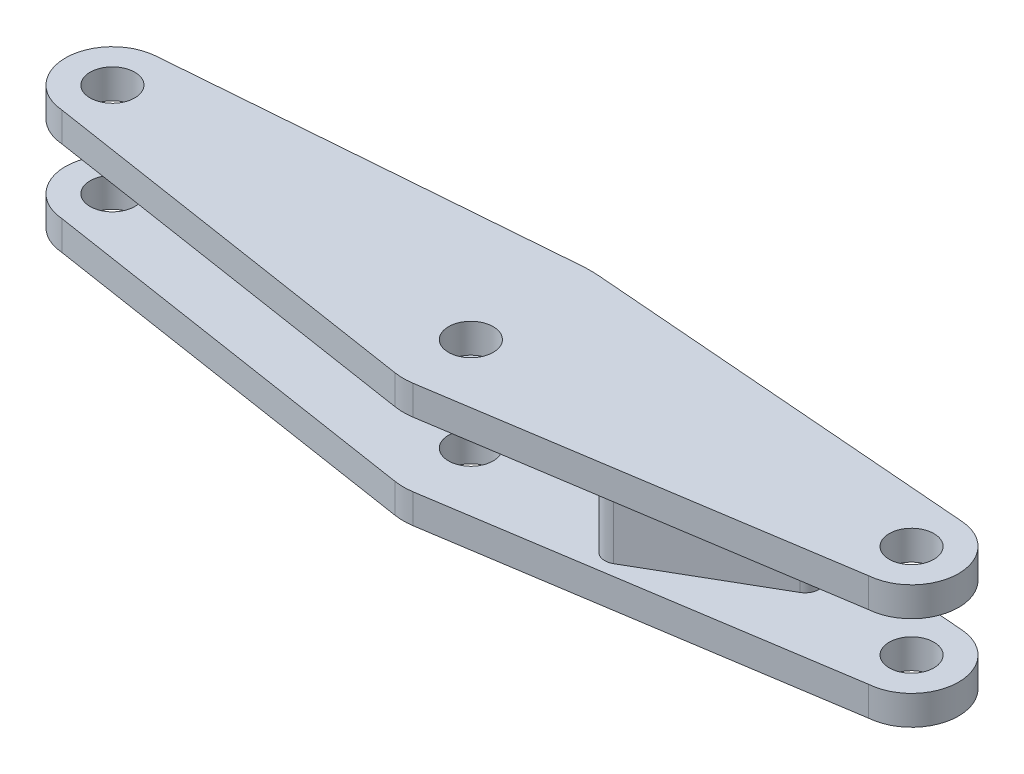
SolidWorks part; units mm, degrees
ref_plane "Front Plane" through (0, 0, 0) normal (0, 0, 1) x (1, 0, 0)
ref_plane "Top Plane" through (0, 0, 0) normal (0, 1, 0) x (1, 0, 0)
ref_plane "Right Plane" through (0, 0, 0) normal (1, 0, 0) x (0, 0, -1)
sketch "Sketch1" plane through (0, 0, 0) normal (0, 1, 0) x (1, 0, 0)
  line L0 (17, 0) -> (-15, 0) construction
  line L1 (0, 0) -> (0, 3.35) construction
  line L2 (0, 0) -> (0, -4.65) construction
  line L3 (-0.394, 3.3189) -> (-17.1576, 1.9938)
  line L4 (0.394, 3.3189) -> (17.1576, 1.9938)
  line L7 (-16.05, 0) -> (-17, 0) construction
  line L10 (-0.3825, -4.5908) -> (-17.1576, -1.9938)
  line L11 (0.3825, -4.5908) -> (17.1576, -1.9938)
  arc A0 (-17.1576, 1.9938) -> (-17.1576, -1.9938) centre (-17, 0) ccw
  circle A1 centre (-17, 0) radius 0.95
  circle A2 centre (17, 0) radius 0.95
  arc A3 (17.1576, -1.9938) -> (17.1576, 1.9938) centre (17, 0) ccw
  arc A4 (0.394, 3.3189) -> (-0.394, 3.3189) centre (0, -1.6656) ccw
  circle A6 centre (0, -1.75) radius 0.95
  arc A7 (0.3825, -4.5908) -> (-0.3825, -4.5908) centre (0, -2.1202) cw
  point P20 (0, 3.3344)
  point P21 (0, 3.3344)
  point P25 (0, 3.35)
  point P26 (0, 3.3344)
  dimension "D1" = 34
  dimension "D4" = 4
  dimension "D5" = 1.9
  dimension "D6" = 4
  dimension "D7" = 1.9
  dimension "D8" = 5
  dimension "D9" = 2.5
  dimension "D10" = 1.75
  dimension "D11" = 1.9
  dimension "D12" = 1.9944
  dimension "D2" = 8
  dimension "D3" = 3.35
extrude "Boss-Extrude1" add sketch "Sketch1" along normal mid plane 5.25
sketch "Sketch3" plane through (0, 0, 0) normal (0, 0, 1) x (1, 0, 0)
  line L0 (-19, 2.625) -> (-19, -2.625) construction
  line L1 (19, 1.375) -> (-19, 1.375)
  line L2 (19, 1.375) -> (19, -1.375)
  line L3 (19, -1.375) -> (-19, -1.375)
  line L4 (-19, 1.375) -> (-19, -1.375)
  line L5 (19, 1.375) -> (-19, -1.375) construction
  line L6 (19, -1.375) -> (-19, 1.375) construction
  line L7 (-17.1576, 2.625) -> (-0.3825, 2.625) construction
  point P0 (0, 0)
  dimension "D1" = 1.25
extrude "Cut-Extrude1" cut sketch "Sketch3" against normal mid plane 10
sketch "Sketch4" plane through (0, 0, 0) normal (0, 1, 0) x (1, 0, 0)
  line L0 (0, 0) -> (12.5282, 0) construction
  line L1 (0.4401, 0.45) -> (12.0213, 0.45) construction
  line L2 (7, -2.4529) -> (12.0213, 0.45) construction
  line L3 (6.6997, -1.9335) -> (11.721, 0.9694)
  line L4 (7.3003, -2.9724) -> (12.3216, -0.0694)
  arc A0 (6.6997, -1.9335) -> (7.3003, -2.9724) centre (7, -2.4529) ccw
  arc A1 (12.3216, -0.0694) -> (11.721, 0.9694) centre (12.0213, 0.45) ccw
  point P6 (9.5106, -1.0015)
  dimension "D2" = 0.6
  dimension "D1" = 5.8
  dimension "D3" = 0.45
  dimension "D4" = 2.4529
extrude "Boss-Extrude3" add sketch "Sketch4" along normal up to next (1.375 mm away) and the other way up to next (2.625 mm away)
